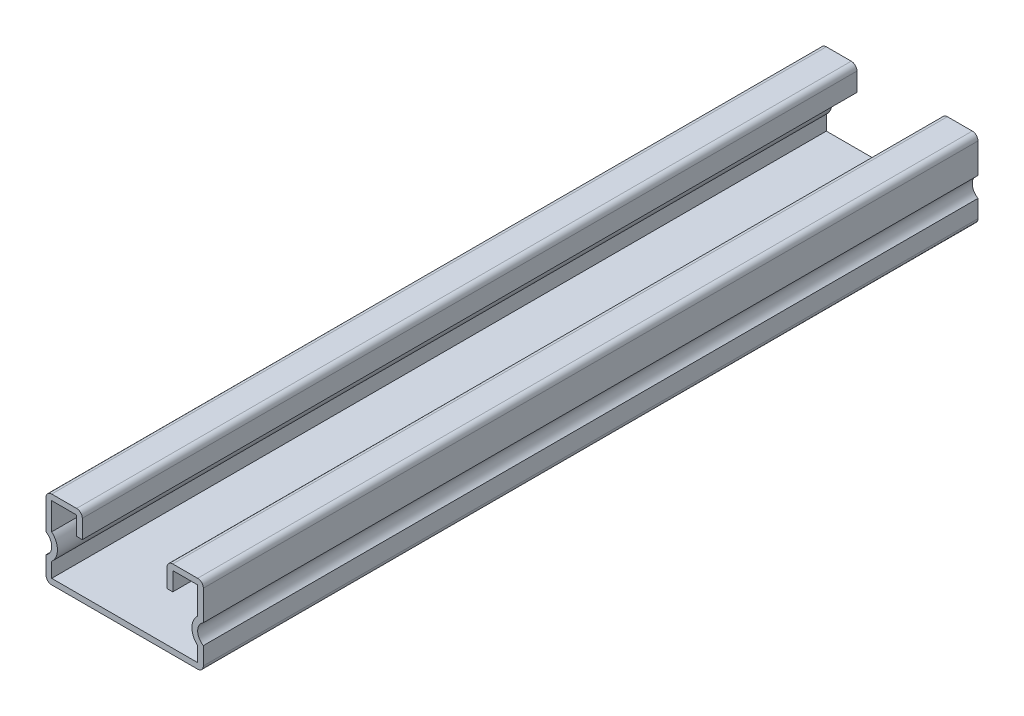
SolidWorks part; units mm, degrees
ref_plane "Plane1" through (0, 0, 0) normal (0, 0, 1) x (1, 0, 0)
ref_plane "Plane2" through (0, 0, 0) normal (0, 1, 0) x (1, 0, 0)
ref_plane "Plane3" through (0, 0, 0) normal (1, 0, 0) x (0, 0, -1)
sketch "Sketch1" plane through (0, 0, 0) normal (0, 0, 1) x (1, 0, 0)
  line L0 (-20.6375, 10.4394) -> (-20.6375, 2.5957)
  line L1 (-20.6375, -2.5957) -> (-20.6375, -7.2136)
  line L2 (-19.1389, -8.7122) -> (19.1389, -8.7122)
  line L3 (20.6375, -7.2136) -> (20.6375, -2.5957)
  line L4 (20.6375, 2.5957) -> (20.6375, 10.4394)
  line L5 (19.1389, 11.938) -> (12.6111, 11.938)
  line L6 (11.1125, 10.4394) -> (11.1125, 5.588)
  line L7 (-19.1389, 11.938) -> (-12.6111, 11.938)
  line L8 (-11.1125, 10.4394) -> (-11.1125, 5.588)
  line L9 (19.1389, -5.2823) -> (19.1389, 6.4389) construction
  line L10 (-19.1389, 6.4389) -> (-19.1389, -5.2823) construction
  line L11 (-12.6111, 10.4394) -> (-12.6111, 5.588)
  line L12 (-19.1389, 10.4394) -> (-12.6111, 10.4394)
  line L13 (-19.1389, 10.4394) -> (-19.1389, 3.351)
  line L14 (-19.1389, -3.351) -> (-19.1389, -7.2136)
  line L15 (-19.1389, -7.2136) -> (19.1389, -7.2136)
  line L16 (19.1389, -7.2136) -> (19.1389, -3.351)
  line L17 (19.1389, 3.351) -> (19.1389, 10.4394)
  line L18 (19.1389, 10.4394) -> (12.6111, 10.4394)
  line L19 (12.6111, 10.4394) -> (12.6111, 5.588)
  line L20 (-12.6111, 5.588) -> (-11.1125, 5.588)
  line L21 (11.1125, 5.588) -> (12.6111, 5.588)
  arc A0 (20.6375, 2.5957) -> (20.6375, -2.5957) centre (22.1361, 0) ccw
  arc A1 (-20.6375, -2.5957) -> (-20.6375, 2.5957) centre (-22.1361, 0) ccw
  arc A2 (-12.6111, 11.938) -> (-11.1125, 10.4394) centre (-12.6111, 10.4394) cw
  arc A3 (-20.6375, 10.4394) -> (-19.1389, 11.938) centre (-19.1389, 10.4394) cw
  arc A4 (-19.1389, -8.7122) -> (-20.6375, -7.2136) centre (-19.1389, -7.2136) cw
  arc A5 (20.6375, -7.2136) -> (19.1389, -8.7122) centre (19.1389, -7.2136) cw
  arc A6 (19.1389, 11.938) -> (20.6375, 10.4394) centre (19.1389, 10.4394) cw
  arc A7 (11.1125, 10.4394) -> (12.6111, 11.938) centre (12.6111, 10.4394) cw
  arc A8 (-19.1389, -3.351) -> (-19.1389, 3.351) centre (-22.1361, 0) ccw
  arc A9 (19.1389, 3.351) -> (19.1389, -3.351) centre (22.1361, 0) ccw
  dimension "D9" = 2.9972
  dimension "D10" = 2.9972
  dimension "D1" = 20.6375
  dimension "Width" = 41.275
  dimension "base" = 8.7122
  dimension "ToeHt" = 11.938
  dimension "D6" = 22.225
  dimension "edge" = 9.525
  dimension "Lip" = 6.35
  dimension "gauge" = 1.4986
extrude "Base-Extrude" add sketch "Sketch1" along normal blind 203.2
extrude "Slot" cut sketch "Sketch2" against normal through all
sketch "Sketch2" plane through (-0.7476, -8.7122, -11.6779) normal (0, -1, 0) x (1, 0, 0)
  line L0 (5.907, 90.2591) -> (5.907, 24.3779)
  line L1 (-4.4118, 24.3779) -> (-4.4118, 90.2591)
  arc A0 (-4.4118, 24.3779) -> (5.907, 24.3779) centre (0.7476, 24.3779) ccw
  arc A1 (5.907, 90.2591) -> (-4.4118, 90.2591) centre (0.7476, 90.2591) ccw
  dimension "D3" = 10.3187
  dimension "D1" = 12.7
  dimension "D2" = 65.8813
pattern_linear "LPattern1" count 2 spacing 101.6 along (0, 0, 1) of "Slot"
equation "\"D1@Sketch1\" = \"Width@Sketch1\" / 2"
equation "\"D6@Sketch1\" = \"Width@Sketch1\" - 2 * \"edge@Sketch1\""
equation "\"D10@Sketch1\" = 2 * \"gauge@Sketch1\""
equation "\"D9@Sketch1\" = \"D10@Sketch1\""
equation "\"D1@LPattern1\" = \"D1@Base-Extrude\" / \"D3@LPattern1\""
